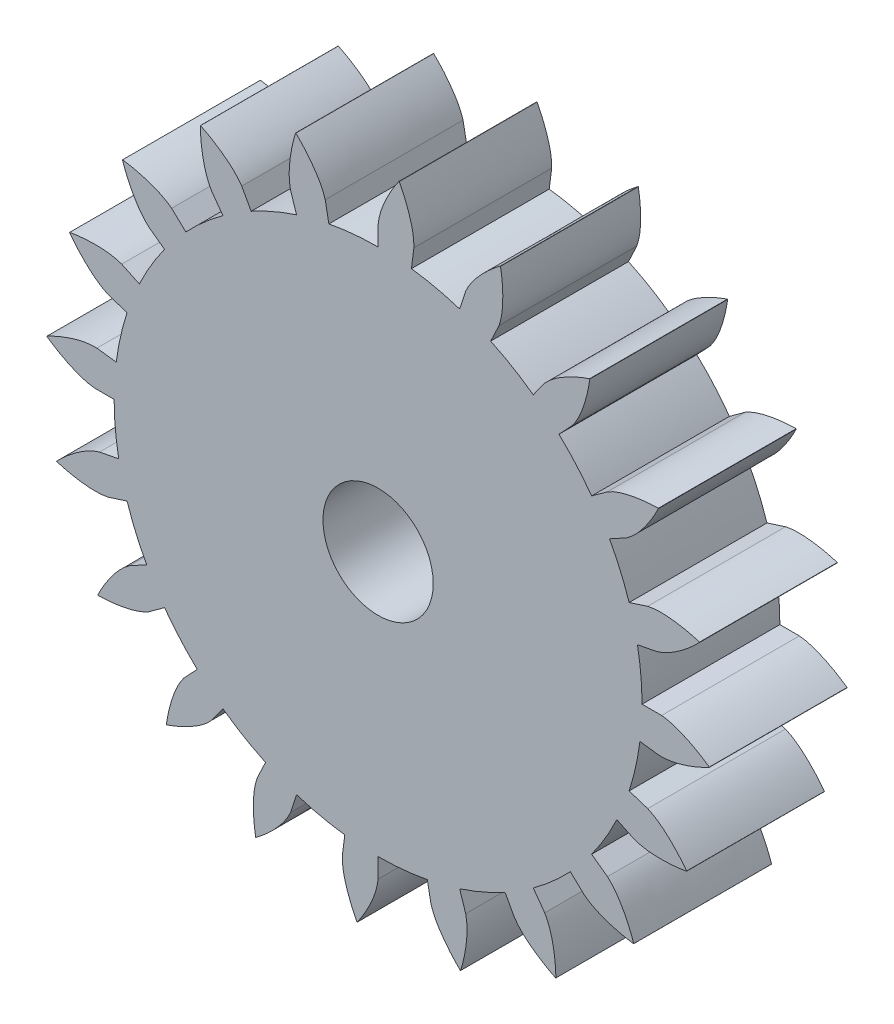
SolidWorks part; units mm, degrees
ref_plane "Front Plane" through (0, 0, 0) normal (0, 0, 1) x (1, 0, 0)
ref_plane "Top Plane" through (0, 0, 0) normal (0, 1, 0) x (1, 0, 0)
ref_plane "Right Plane" through (0, 0, 0) normal (1, 0, 0) x (0, 0, -1)
sketch "Sketch7" plane through (0, 0, 0) normal (0, 0, 1) x (1, 0, 0)
  line L0 (0, 30.8547) -> (6.2474, 30.2156) construction
  line L1 (6.2474, 30.2156) -> (12.236, 28.3248) construction
  line L2 (12.236, 28.3248) -> (17.7177, 25.2606) construction
  line L3 (17.7177, 25.2606) -> (22.4654, 21.1499) construction
  line L4 (6.2474, 30.2156) -> (0.0975, 31.4872) construction
  line L5 (12.236, 28.3248) -> (0.7058, 33.3057) construction
  line L6 (17.7177, 25.2606) -> (2.2935, 36.079) construction
  line L7 (22.4654, 21.1499) -> (5.2465, 39.4398) construction
  line L8 (0.5074, 32.8307) -> (3.6412, 32.6321) construction
  line L9 (2.0743, 32.7314) -> (0, 0) construction
  line L10 (0, 30.8547) -> (0, 0)
  line L11 (0, 0) -> (3.8951, 30.6078)
  circle A0 centre (0, 0) radius 36.1181
  circle A1 centre (0, 0) radius 32.8346 construction
  circle A2 centre (0, 0) radius 30.8547 construction
  circle A3 centre (0, 0) radius 28.7303
  circle A4 centre (0, 0) radius 6
  spline S0 degree 3 poles (0, 30.8547) (0.0845, 31.7057) (1.1882, 34.9741) (3.4004, 37.6876) (5.2465, 39.4398) knots 0 0 0 0 0.250074 1 1 1 1
  spline S1 degree 3 poles (3.8951, 30.6078) (3.9187, 31.4627) (3.2364, 34.8443) (1.3845, 37.8154) (-0.2256, 39.7866) knots 0 0 0 0 0.250074 1 1 1 1
  dimension "D1" = 6.28
  dimension "D2" = 12.56
  dimension "D3" = 18.84
  dimension "D4" = 25.12
extrude "Boss-Extrude7" add sketch "Sketch7" along normal blind 15 contours L10 A3 L11 | L11 A3 L10 | L11 S1 A0 S0 L10 A3
pattern_circular "CirPattern2" count 20 over 360 about axis through (0, 0, 15) along (0, 0, -1) of "Boss-Extrude7"
